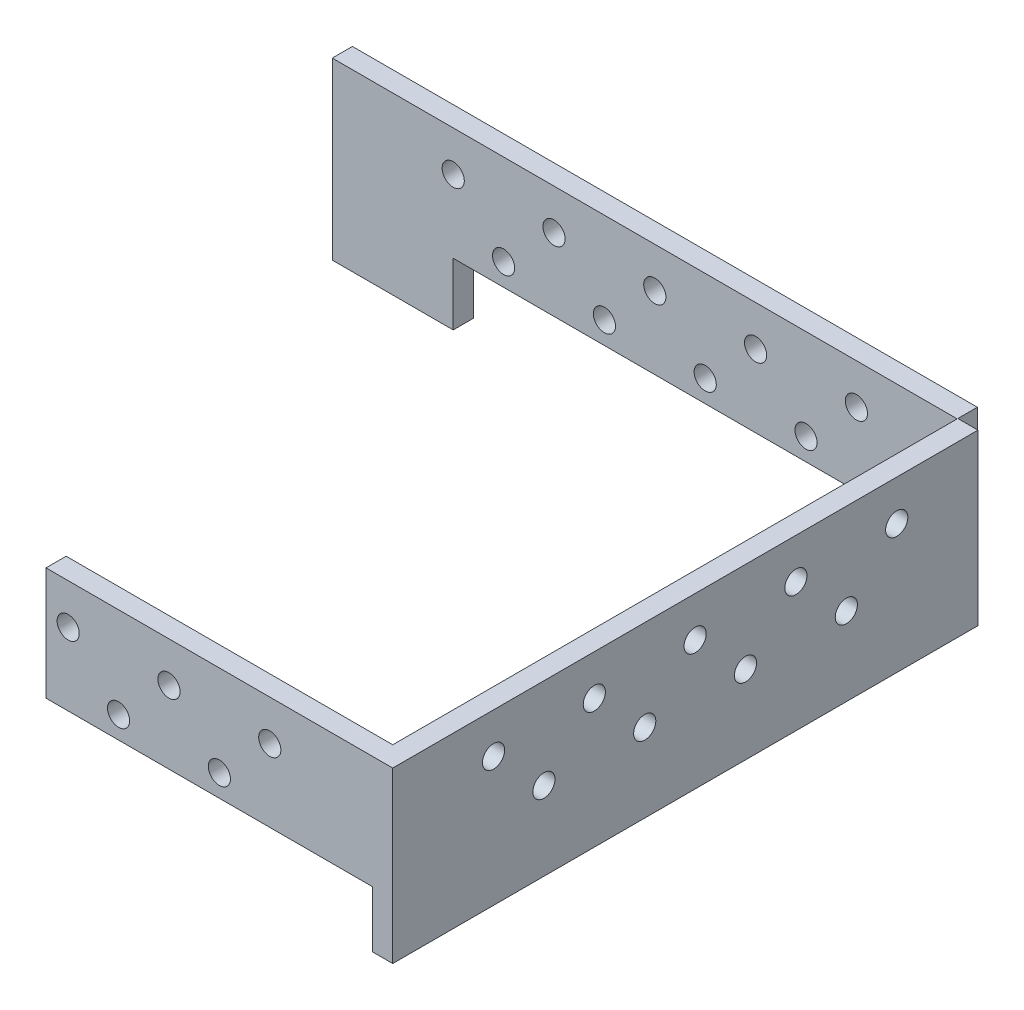
SolidWorks part; units mm, degrees
ref_plane "Front Plane" through (0, 0, 0) normal (0, 0, 1) x (1, 0, 0)
ref_plane "Top Plane" through (0, 0, 0) normal (0, 1, 0) x (1, 0, 0)
ref_plane "Right Plane" through (0, 0, 0) normal (1, 0, 0) x (0, 0, -1)
ref_plane "Plane1" through (-5, 0, 0) normal (-1, 0, 0) x (0, -1, 0)
sketch "Sketch1" plane through (-5, 0, 0) normal (-1, 0, 0) x (0, -1, 0)
  line L0 (42, 0) -> (0, 0)
  line L1 (0, 0) -> (0, -145.1613)
  line L2 (0, -145.1613) -> (42, -145.1613)
  line L3 (42, -145.1613) -> (42, 0)
  dimension "D1" = 42
extrude "Boss-Extrude1" add sketch "Sketch1" against normal blind 5
ref_plane "Plane2" through (0, 0, -150) normal (0, 0, -1) x (-1, 0, 0)
sketch "Sketch2" plane through (0, 0, -150) normal (0, 0, -1) x (-1, 0, 0)
  line L0 (130, -43.4) -> (160, -43.4)
  line L1 (160, -43.4) -> (160, 0)
  line L2 (160, 0) -> (5, 0)
  line L3 (5, 0) -> (5, -28)
  line L4 (5, -28) -> (130, -28)
  line L5 (130, -28) -> (130, -43.4)
extrude "Boss-Extrude2" add sketch "Sketch2" against normal blind 5
sketch "Sketch3" plane through (-5, 0, 0) normal (-1, 0, 0) x (0, 0, 1)
  line L0 (0, -28) -> (-5, -28)
  line L1 (-5, -28) -> (-5, 0)
  line L2 (-5, 0) -> (0, 0)
  line L3 (0, 0) -> (0, -28)
extrude "Boss-Extrude3" add sketch "Sketch3" along normal blind 81
hole_wizard "Ø5.5 (5.5) Diameter Hole1" positions "Sketch5" profile "Sketch4" hole size "Ø5.5" standard "ANSI Metric" end condition through all
sketch "Sketch5" plane through (-5, 0, 0) normal (-1, 0, 0) x (0, 0, 1)
  point P0 (-37.5, -22.5)
  point P1 (-25, -10)
  point P2 (-50, -10)
  point P3 (-62.5, -22.5)
  point P4 (-75, -10)
  point P5 (-87.5, -22.5)
  point P6 (-112.5, -22.5)
  point P7 (-100, -10)
  point P8 (-125, -10)
sketch "Sketch4" plane through (-5, -22.5, -37.5) normal (0, 1, 0) x (0, 0, 1)
  line L0 (0, 0) -> (0, 5)
  line L1 (0, 5) -> (2.75, 5)
  line L2 (2.75, 5) -> (2.75, 0)
  line L5 (2.75, 0) -> (0, 0)
  line L11 (0, -6.35) -> (0, 107.95) construction
  dimension "Thru Hole Dia." = 5.5
  dimension "Thru Hole Depth" = 5
hole_wizard "Ø5.5 (5.5) Diameter Hole2" positions "Sketch7" profile "Sketch6" hole size "Ø5.5" standard "ANSI Metric"
sketch "Sketch7" plane through (0, 0, -145) normal (0, 0, 1) x (1, 0, 0)
  point P0 (-30, -10)
  point P1 (-42.5, -22.5)
  point P2 (-67.5, -22.5)
  point P3 (-55, -10)
  point P4 (-80, -10)
  point P5 (-92.5, -22.5)
  point P6 (-117.5, -22.5)
  point P7 (-105, -10)
  point P8 (-130, -10)
sketch "Sketch6" plane through (-30, -10, -145) normal (1, 0, 0) x (0, -1, 0)
  line L0 (0, 0) -> (0, 5)
  line L1 (0, 5) -> (2.75, 5)
  line L2 (2.75, 5) -> (2.75, 0)
  line L5 (2.75, 0) -> (0, 0)
  line L11 (0, -6.35) -> (0, 107.95) construction
  dimension "Thru Hole Dia." = 5.5
  dimension "Thru Hole Depth" = 5
hole_wizard "Ø5.5 (5.5) Diameter Hole3" positions "Sketch9" profile "Sketch8" hole size "Ø5.5" standard "ANSI Metric"
sketch "Sketch9" plane through (0, 0, -5) normal (0, 0, -1) x (-1, 0, 0)
  point P0 (80.5, -10)
  point P1 (68, -22.5)
  point P2 (43, -22.5)
  point P3 (55.5, -10)
  point P4 (30.5, -10)
sketch "Sketch8" plane through (-80.5, -10, -5) normal (1, 0, 0) x (0, 1, 0)
  line L0 (0, 0) -> (0, 5)
  line L1 (0, 5) -> (2.75, 5)
  line L2 (2.75, 5) -> (2.75, 0)
  line L5 (2.75, 0) -> (0, 0)
  line L11 (0, -6.35) -> (0, 107.95) construction
  dimension "Thru Hole Dia." = 5.5
  dimension "Thru Hole Depth" = 5
